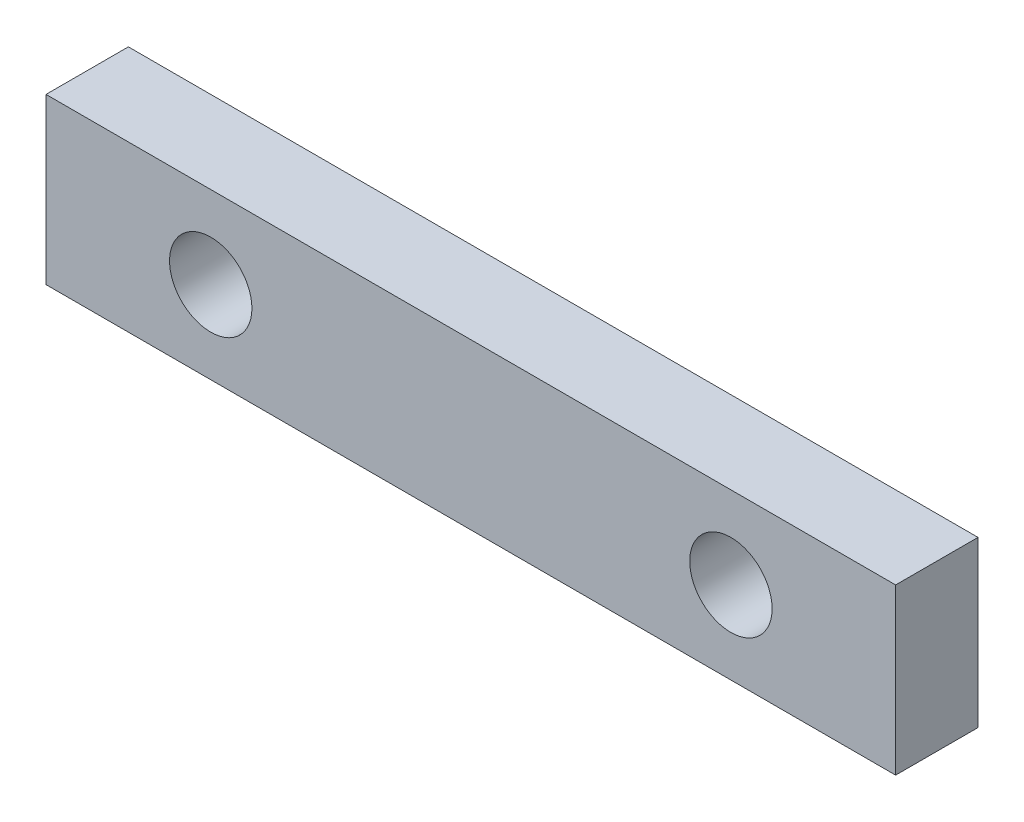
SolidWorks part; units mm, degrees
material "Balsa"
ref_plane "Front" through (0, 0, 0) normal (0, 0, 1) x (1, 0, 0)
ref_plane "Top" through (0, 0, 0) normal (0, 1, 0) x (1, 0, 0)
ref_plane "Right" through (0, 0, 0) normal (1, 0, 0) x (0, 0, -1)
sketch "Sketch3" plane through (0, 0, 0) normal (0, 0, 1) x (1, 0, 0)
  line L0 (0, 3.175) -> (32.75, 3.175) construction
  line L1 (0, 0) -> (32.75, 0)
  line L2 (0, 0) -> (0, 6.35)
  line L3 (0, 6.35) -> (32.75, 6.35)
  line L4 (32.75, 0) -> (32.75, 6.35)
  line L5 (11.1125, 3.175) -> (11.1125, 0) construction
  line L6 (11.6125, 3.175) -> (11.6125, 0) construction
  line L7 (21.1375, 3.175) -> (21.1375, 0) construction
  line L8 (21.6375, 3.175) -> (21.6375, 0) construction
  line L9 (11.1125, 1.5875) -> (11.6125, 1.5875) construction
  line L10 (21.1375, 1.5875) -> (21.6375, 1.5875) construction
  circle A0 centre (6.35, 3.175) radius 1.5875
  circle A1 centre (26.4, 3.175) radius 1.5875
  circle A2 centre (6.35, 3.175) radius 4.7625 construction
  circle A3 centre (16.375, 3.175) radius 4.7625 construction
  circle A4 centre (26.4, 3.175) radius 4.7625 construction
  dimension "D2" = 3.175
  dimension "D3" = 9.525
  dimension "D5" = 6.35
  dimension "D1" = 6.35
  dimension "D4" = 6.35
  dimension "D6" = 0.5
extrude "Boss-Extrude1" add sketch "Sketch3" along normal blind 3.175
